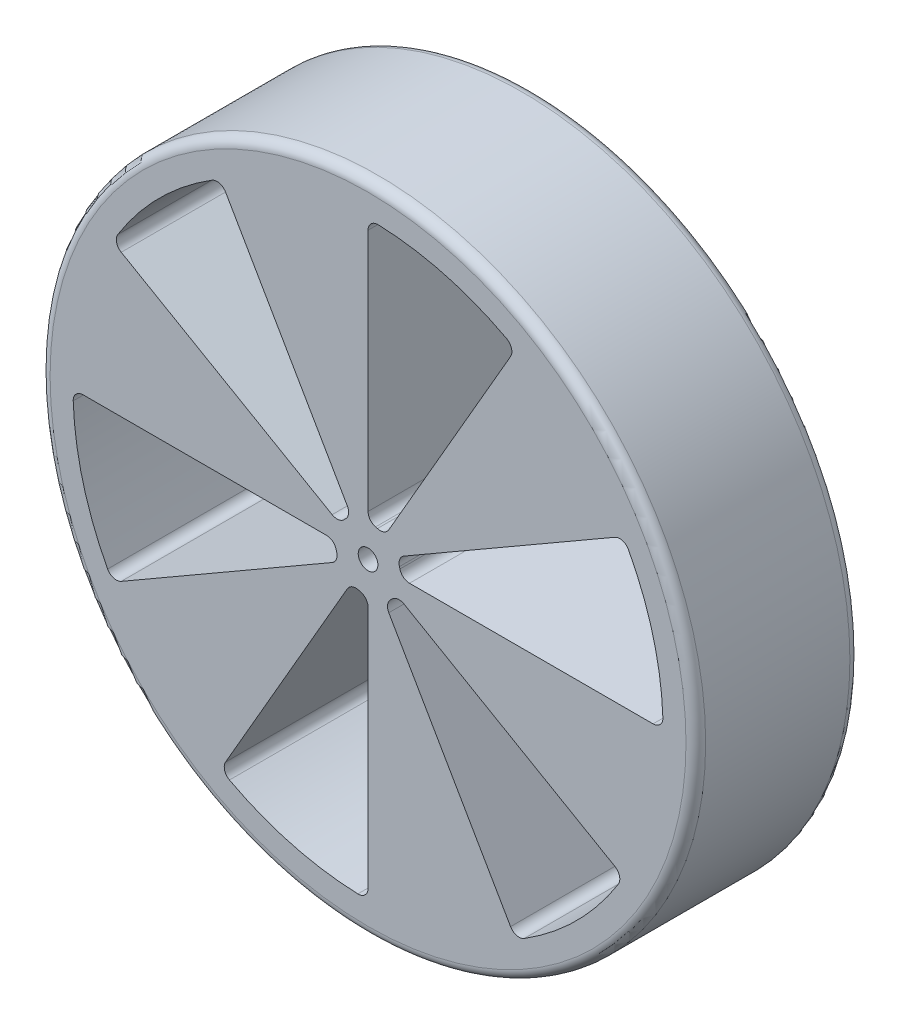
SolidWorks part; units mm, degrees
ref_plane "Front Plane" through (0, 0, 0) normal (0, 0, 1) x (1, 0, 0)
ref_plane "Top Plane" through (0, 0, 0) normal (0, 1, 0) x (1, 0, 0)
ref_plane "Right Plane" through (0, 0, 0) normal (1, 0, 0) x (0, 0, -1)
sketch "Sketch1" plane through (0, 0, 0) normal (0, 0, 1) x (1, 0, 0)
  circle A0 centre (0, 0) radius 100
  dimension "D1" = 200
extrude "Boss-Extrude1" add sketch "Sketch1" along normal blind 50
sketch "Sketch2" plane through (0, 0, 50) normal (0, 0, 1) x (1, 0, 0)
  line L0 (0, 10) -> (0, 90)
  line L1 (5, 8.6603) -> (45, 77.9423)
  circle A0 centre (0, 0) radius 10
  circle A1 centre (0, 0) radius 90
  circle A2 centre (0, 0) radius 100 construction
  dimension "D1" = 20
  dimension "D2" = 10
  dimension "D3" = 30
extrude "Cut-Extrude1" cut sketch "Sketch2" against normal through all contours L1 A1 L0 A0
pattern_circular "CirPattern1" count 6 over 360 about axis through (0, 0, 0) along (0, 0, 1) of "Cut-Extrude1"
fillet "Fillet1" radius 3 26 edges at (0, 90, 25) (45, 77.9423, 25) (5, 8.6603, 25) (-8.6603, 5, 25) (-77.9423, 45, 25) (-45, 77.9423, 25) (-5, 8.6603, 25) (0, -10, 25) (0, -90, 25) (-45, -77.9423, 25) (-5, -8.6603, 25) (-8.6603, -5, 25) (-77.9423, -45, 25) (-90, 0, 25) (-10, 0, 25) (8.6603, -5, 25) (77.9423, -45, 25) (45, -77.9423, 25) (5, -8.6603, 25) (8.6603, 5, 25) (77.9423, 45, 25) (90, 0, 25) (10, 0, 25) (0, 10, 25) (100, 0, 0) (100, 0, 50)
sketch "Sketch3" plane through (0, 0, 50) normal (0, 0, 1) x (1, 0, 0)
  circle A0 centre (0, 0) radius 3
  dimension "D1" = 6
extrude "Cut-Extrude2" cut sketch "Sketch3" against normal through all
